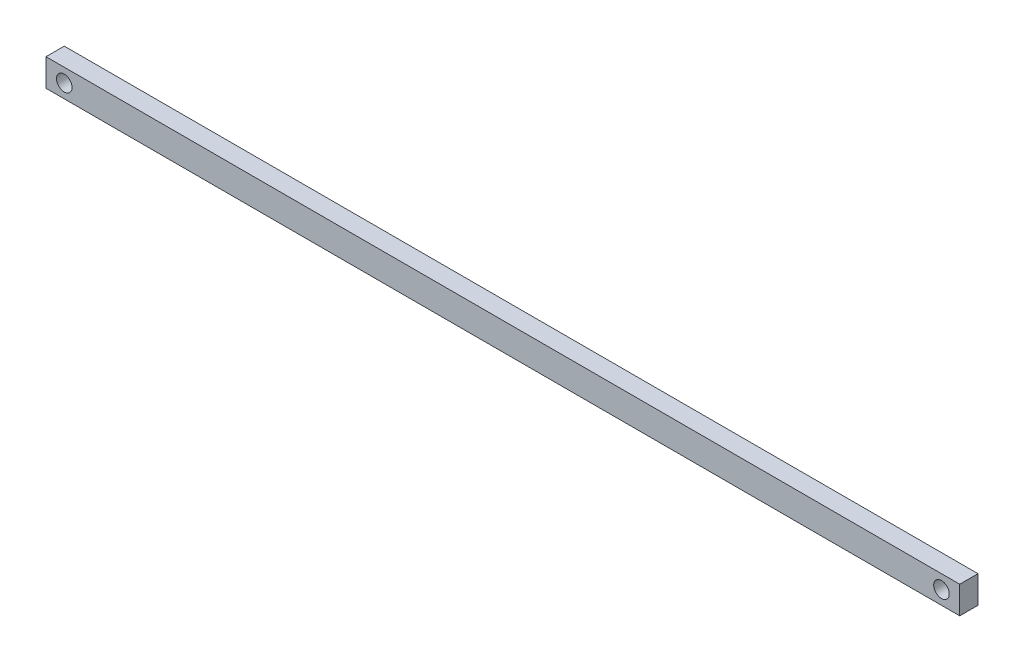
SolidWorks part; units mm, degrees
material "ASTM A36 Steel"
ref_plane "Front Plane" through (0, 0, 0) normal (0, 0, 1) x (1, 0, 0)
ref_plane "Top Plane" through (0, 0, 0) normal (0, 1, 0) x (1, 0, 0)
ref_plane "Right Plane" through (0, 0, 0) normal (1, 0, 0) x (0, 0, -1)
sketch "Sketch1" plane through (0, 0, 0) normal (0, 0, 1) x (1, 0, 0)
  line L0 (55, 0) -> (-55, 0) construction
  line L1 (0, 0) -> (500, 0)
  line L2 (0, 0) -> (0, 15)
  line L3 (0, 15) -> (500, 15)
  line L4 (500, 0) -> (500, 15)
  dimension "D1" = 500
  dimension "D2" = 15
extrude "Boss-Extrude1" add sketch "Sketch1" along normal blind 10
sketch "Sketch2" plane through (0, 0, 10) normal (0, 0, 1) x (1, 0, 0)
  line L0 (0, 15) -> (0, 0) construction
  line L1 (0, 7.5) -> (-51.7723, 7.5) construction
  line L3 (500, 0) -> (500, 15) construction
  circle A0 centre (10, 7.5) radius 4.255
  circle A1 centre (490, 7.5) radius 4.255
  dimension "D1" = 8.51
  dimension "D2" = 10
  dimension "D3" = 10
extrude "Cut-Extrude1" cut sketch "Sketch2" against normal up to surface (10 mm away) up to face at (250, 7.5, 0)
